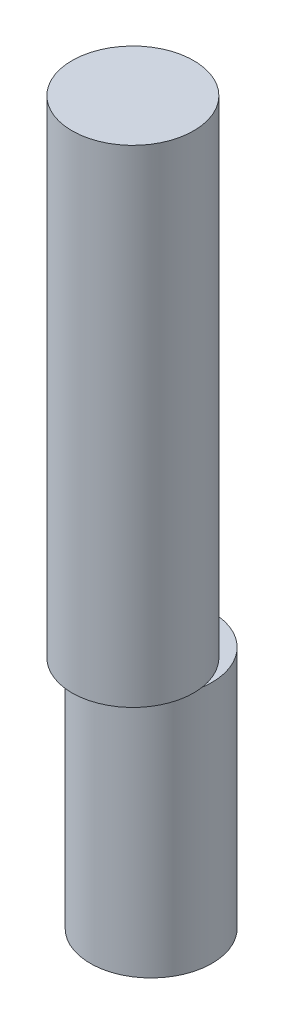
SolidWorks part; units mm, degrees
ref_plane "Front Plane" through (0, 0, 0) normal (0, 0, 1) x (1, 0, 0)
ref_plane "Top Plane" through (0, 0, 0) normal (0, 1, 0) x (1, 0, 0)
ref_plane "Right Plane" through (0, 0, 0) normal (1, 0, 0) x (0, 0, -1)
sketch "Sketch1" plane through (0, 0, 0) normal (0, 1, 0) x (1, 0, 0)
  circle A0 centre (0, 0) radius 6.35
  dimension "D1" = 12.7
extrude "Boss-Extrude1" add sketch "Sketch1" along normal blind 50.8
sketch "Sketch3" plane through (0, 0, 0) normal (0, -1, 0) x (1, 0, 0)
  circle A0 centre (0, -1.905) radius 6.35
  dimension "D2" = 12.7
  dimension "D1" = 1.905
extrude "Boss-Extrude2" add sketch "Sketch3" along normal blind 25.4
